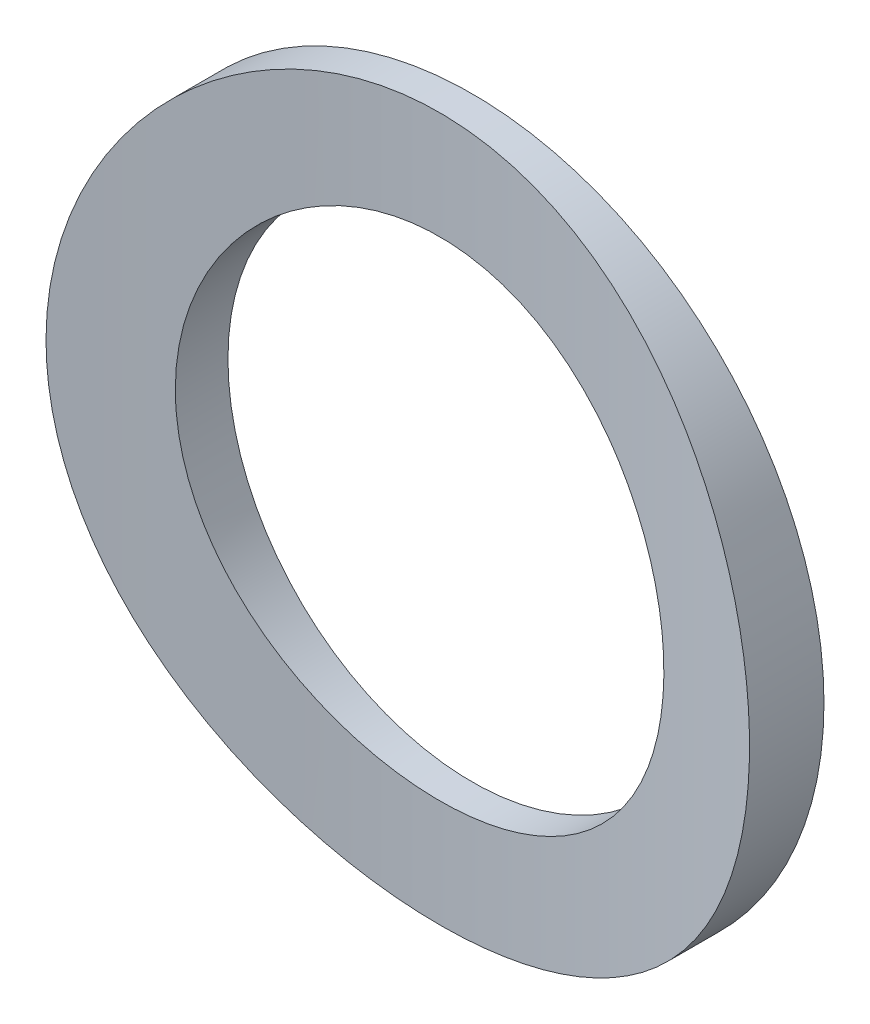
SolidWorks part; units mm, degrees
material "PTFE (general)"
ref_plane "Front Plane" through (0, 0, 0) normal (0, 0, 1) x (1, 0, 0)
ref_plane "Top Plane" through (0, 0, 0) normal (0, 1, 0) x (1, 0, 0)
ref_plane "Right Plane" through (0, 0, 0) normal (1, 0, 0) x (0, 0, -1)
sketch "Sketch1" plane through (0, 0, 0) normal (0, 0, 1) x (1, 0, 0)
  circle A0 centre (0, 0) radius 10.8
  circle A1 centre (0, 0) radius 7.5
  dimension "D1" = 21.6
  dimension "D2" = 15
extrude "Boss-Extrude1" add sketch "Sketch1" along normal blind 30
sketch "Sketch2" plane through (0, 0, 0) normal (0, 1, 0) x (1, 0, 0)
  line L0 (10.8, 0) -> (-10.8, 0) construction
  circle A0 centre (0, -47) radius 46
  dimension "D1" = 92
  dimension "D2" = 47
extrude "Cut-Extrude1" cut sketch "Sketch2" against normal through all both and the other way through all
